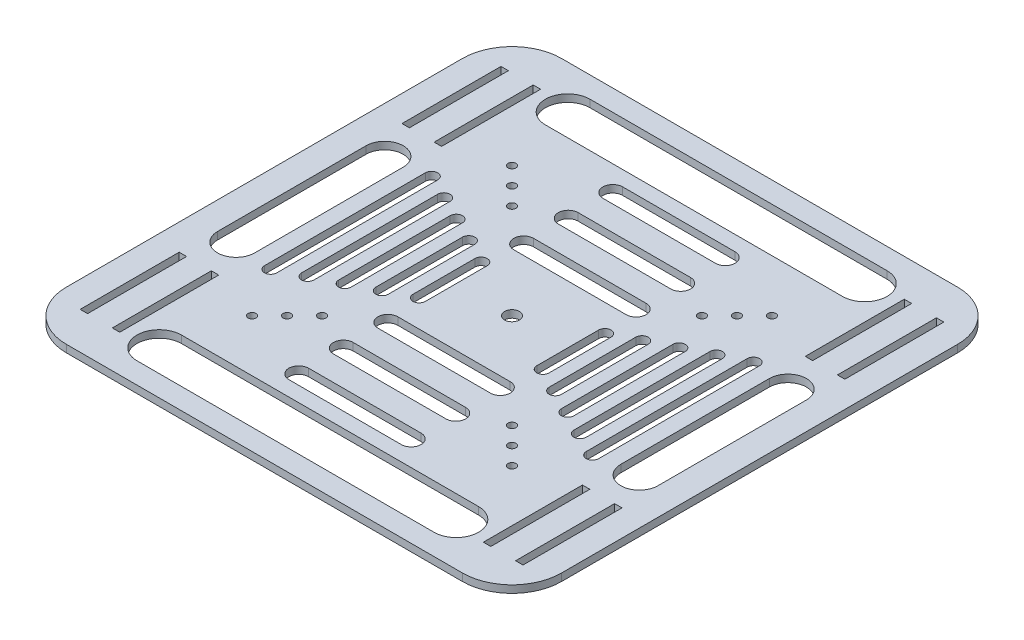
SolidWorks part; units mm, degrees
ref_plane "前视基准面" through (0, 0, 0) normal (0, 0, 1) x (1, 0, 0)
ref_plane "上视基准面" through (0, 0, 0) normal (0, 1, 0) x (1, 0, 0)
ref_plane "右视基准面" through (0, 0, 0) normal (1, 0, 0) x (0, 0, -1)
sketch "草图2" plane through (0, 0, 0) normal (0, 1, 0) x (1, 0, 0)
  line L0 (100, 100) -> (100, -100)
  line L1 (100, 100) -> (-100, 100)
  line L2 (100, -100) -> (-100, -100)
  line L3 (-100, 100) -> (-100, -100)
  line L4 (100, 100) -> (-100, -100) construction
  line L5 (100, -100) -> (-100, 100) construction
  line L6 (0, 65) -> (0, -65) construction
  line L7 (-68.9429, -68.9429) -> (68.9429, 68.9429) construction
  line L8 (-68.9429, 68.9429) -> (68.9429, -68.9429) construction
  line L9 (68.9429, 68.9429) -> (68.9429, -68.9429)
  line L10 (-68.9429, -68.9429) -> (-68.9429, 68.9429)
  line L11 (68.9429, 68.9429) -> (-68.9429, 68.9429)
  line L12 (-68.9429, -68.9429) -> (68.9429, -68.9429)
  line L13 (68.9429, 0) -> (81.4429, 0)
  line L14 (81.4429, 10) -> (81.4429, -10) construction
  line L15 (81.4429, 0) -> (76.4429, 0) construction
  line L16 (86.4429, -10) -> (89.4429, -10) construction
  line L17 (76.4429, 10) -> (73.4429, 10) construction
  line L18 (76.4429, 10) -> (76.4429, -10) construction
  line L19 (76.4429, -10) -> (73.4429, -10) construction
  line L20 (73.4429, 10) -> (73.4429, -10) construction
  line L21 (89.4429, 10) -> (89.4429, -10) construction
  line L22 (86.4429, 10) -> (86.4429, -10) construction
  line L23 (86.4429, 10) -> (89.4429, 10) construction
  line L24 (0, -65) -> (0, -100)
  line L25 (-60, -82.5) -> (60, -82.5) construction
  line L34 (-60, 82.5) -> (60, 82.5) construction
  line L35 (-81.4429, -10) -> (-81.4429, 10) construction
  line L36 (-81.4429, 0) -> (-76.4429, 0) construction
  line L37 (-86.4429, 10) -> (-89.4429, 10) construction
  line L38 (-76.4429, -10) -> (-73.4429, -10) construction
  line L39 (-76.4429, -10) -> (-76.4429, 10) construction
  line L40 (-76.4429, 10) -> (-73.4429, 10) construction
  line L41 (-73.4429, -10) -> (-73.4429, 10) construction
  line L42 (-89.4429, -10) -> (-89.4429, 10) construction
  line L43 (-86.4429, -10) -> (-86.4429, 10) construction
  line L44 (-86.4429, -10) -> (-89.4429, -10) construction
  line L45 (-60, 73.5) -> (60, 73.5)
  line L46 (-60, -73.5) -> (60, -73.5)
  line L47 (-60, -91.5) -> (60, -91.5)
  line L57 (0, 65) -> (73.4429, 65) construction
  line L58 (73.4429, 85) -> (73.4429, 45)
  line L59 (73.4429, 85) -> (76.4429, 85)
  line L60 (76.4429, 85) -> (76.4429, 45)
  line L61 (76.4429, 45) -> (73.4429, 45)
  line L62 (86.4429, 45) -> (89.4429, 45)
  line L63 (86.4429, 85) -> (86.4429, 45)
  line L64 (89.4429, 85) -> (86.4429, 85)
  line L65 (89.4429, 85) -> (89.4429, 45)
  line L66 (73.4429, -85) -> (73.4429, -45)
  line L67 (89.4429, -85) -> (89.4429, -45)
  line L68 (89.4429, -85) -> (86.4429, -85)
  line L69 (86.4429, -85) -> (86.4429, -45)
  line L70 (86.4429, -45) -> (89.4429, -45)
  line L71 (76.4429, -45) -> (73.4429, -45)
  line L72 (76.4429, -85) -> (76.4429, -45)
  line L73 (73.4429, -85) -> (76.4429, -85)
  line L74 (-73.4429, -85) -> (-76.4429, -85)
  line L75 (-76.4429, -85) -> (-76.4429, -45)
  line L76 (-76.4429, -45) -> (-73.4429, -45)
  line L77 (-86.4429, -45) -> (-89.4429, -45)
  line L78 (-86.4429, -85) -> (-86.4429, -45)
  line L79 (-89.4429, -85) -> (-86.4429, -85)
  line L80 (-89.4429, -85) -> (-89.4429, -45)
  line L81 (-73.4429, -85) -> (-73.4429, -45)
  line L82 (-89.4429, 85) -> (-89.4429, 45)
  line L83 (-89.4429, 85) -> (-86.4429, 85)
  line L84 (-86.4429, 85) -> (-86.4429, 45)
  line L85 (-86.4429, 45) -> (-89.4429, 45)
  line L86 (-76.4429, 45) -> (-73.4429, 45)
  line L87 (-76.4429, 85) -> (-76.4429, 45)
  line L88 (-73.4429, 85) -> (-76.4429, 85)
  line L89 (-73.4429, 85) -> (-73.4429, 45)
  line L90 (22.7145, 27.4289) -> (-22.7145, 27.4289) construction
  line L91 (22.7145, 23.4289) -> (-22.7145, 23.4289)
  line L96 (-45.4289, 45.4289) -> (0, 45.4289)
  line L99 (22.7145, 31.4289) -> (-22.7145, 31.4289)
  line L102 (22.7145, 63.4289) -> (-22.7145, 63.4289) construction
  line L108 (0, 0) -> (-52.5, 0)
  line L111 (-10, 86.4429) -> (10, 86.4429) [skipped]
  line L112 (-10, 81.4429) -> (10, 81.4429) [skipped]
  line L113 (0, 81.4429) -> (0, 76.4429) [skipped]
  line L114 (10, 86.4429) -> (10, 89.4429) [skipped]
  line L115 (-10, 76.4429) -> (-10, 73.4429) [skipped]
  line L116 (-10, 76.4429) -> (10, 76.4429) [skipped]
  line L117 (10, 76.4429) -> (10, 73.4429) [skipped]
  line L118 (-10, 73.4429) -> (10, 73.4429) [skipped]
  line L119 (-10, 89.4429) -> (10, 89.4429) [skipped]
  line L120 (-10, 86.4429) -> (-10, 89.4429) [skipped]
  line L121 (0, 68.9429) -> (0, 81.4429) construction
  line L122 (10, -81.4429) -> (-10, -81.4429) [skipped]
  line L123 (0, -81.4429) -> (0, -76.4429) [skipped]
  line L124 (-10, -86.4429) -> (-10, -89.4429) [skipped]
  line L125 (10, -76.4429) -> (-10, -76.4429) [skipped]
  line L126 (10, -89.4429) -> (-10, -89.4429) [skipped]
  line L127 (10, -86.4429) -> (-10, -86.4429) [skipped]
  line L128 (10, -86.4429) -> (10, -89.4429) [skipped]
  line L129 (10, -76.4429) -> (10, -73.4429) [skipped]
  line L130 (-10, -76.4429) -> (-10, -73.4429) [skipped]
  line L131 (10, -73.4429) -> (-10, -73.4429) [skipped]
  line L132 (0, -68.9429) -> (0, -81.4429) construction
  line L135 (22.7145, 45.4289) -> (-22.7145, 45.4289) construction
  line L136 (22.7145, 41.4289) -> (-22.7145, 41.4289)
  line L137 (-52.5, 0) -> (-52.5, 52.5)
  line L138 (22.7145, 49.4289) -> (-22.7145, 49.4289)
  line L139 (22.7145, 59.4289) -> (-22.7145, 59.4289)
  line L144 (22.7145, 67.4289) -> (-22.7145, 67.4289)
  line L147 (22.7145, -27.4289) -> (-22.7145, -27.4289) construction
  line L150 (22.7145, -23.4289) -> (-22.7145, -23.4289)
  line L153 (22.7145, -31.4289) -> (-22.7145, -31.4289)
  line L156 (22.7145, -45.4289) -> (-22.7145, -45.4289) construction
  line L159 (22.7145, -41.4289) -> (-22.7145, -41.4289)
  line L162 (22.7145, -49.4289) -> (-22.7145, -49.4289)
  line L165 (22.7145, -63.4289) -> (-22.7145, -63.4289) construction
  line L168 (22.7145, -59.4289) -> (-22.7145, -59.4289)
  line L169 (22.7145, -67.4289) -> (-22.7145, -67.4289)
  line L170 (0, 0) -> (25, 0)
  line L171 (25, 0) -> (25, 25)
  line L172 (25, 0) -> (35, 0)
  line L177 (35, 0) -> (45, 0)
  line L180 (45, 0) -> (55, 0)
  line L183 (55, 0) -> (65, 0)
  line L184 (65, 0) -> (65, 65)
  line L185 (55, 0) -> (55, 55)
  line L186 (45, 0) -> (45, 45)
  line L187 (35, 0) -> (35, 35)
  line L188 (25, -12.5) -> (25, 12.5) construction
  line L189 (22.5, -12.5) -> (22.5, 12.5)
  line L190 (27.5, -12.5) -> (27.5, 12.5)
  line L191 (35, -17.5) -> (35, 17.5) construction
  line L192 (32.5, -17.5) -> (32.5, 17.5)
  line L193 (37.5, -17.5) -> (37.5, 17.5)
  line L194 (45, -22.5) -> (45, 22.5) construction
  line L195 (42.5, -22.5) -> (42.5, 22.5)
  line L196 (47.5, -22.5) -> (47.5, 22.5)
  line L197 (55, -27.5) -> (55, 27.5) construction
  line L198 (52.5, -27.5) -> (52.5, 27.5)
  line L199 (57.5, -27.5) -> (57.5, 27.5)
  line L200 (65, -32.5) -> (65, 32.5) construction
  line L201 (62.5, -32.5) -> (62.5, 32.5)
  line L202 (67.5, -32.5) -> (67.5, 32.5)
  line L203 (-25, -12.5) -> (-25, 12.5) construction
  line L204 (-22.5, -12.5) -> (-22.5, 12.5)
  line L205 (-27.5, -12.5) -> (-27.5, 12.5)
  line L206 (-35, -17.5) -> (-35, 17.5) construction
  line L207 (-32.5, -17.5) -> (-32.5, 17.5)
  line L208 (-37.5, -17.5) -> (-37.5, 17.5)
  line L209 (-45, -22.5) -> (-45, 22.5) construction
  line L210 (-42.5, -22.5) -> (-42.5, 22.5)
  line L211 (-47.5, -22.5) -> (-47.5, 22.5)
  line L212 (-55, -27.5) -> (-55, 27.5) construction
  line L213 (-52.5, -27.5) -> (-52.5, 27.5)
  line L214 (-57.5, -27.5) -> (-57.5, 27.5)
  line L215 (-65, -32.5) -> (-65, 32.5) construction
  line L216 (-62.5, -32.5) -> (-62.5, 32.5)
  line L217 (-67.5, -32.5) -> (-67.5, 32.5)
  line L218 (-68.9429, 0) -> (-81.4429, 0) construction
  line L219 (-60, 91.5) -> (60, 91.5)
  line L220 (81.4429, 30) -> (81.4429, -30) construction
  line L221 (-81.4429, 30) -> (-81.4429, -30) construction
  line L222 (88.9429, 30) -> (88.9429, -30)
  line L223 (73.9429, 30) -> (73.9429, -30)
  line L224 (-88.9429, 30) -> (-88.9429, -30)
  line L225 (-73.9429, 30) -> (-73.9429, -30)
  arc A14 (-60, -73.5) -> (-60, -91.5) centre (-60, -82.5) ccw
  arc A15 (60, -91.5) -> (60, -73.5) centre (60, -82.5) ccw
  circle A18 centre (-52.5, 52.5) radius 1.6
  circle A19 centre (-45.4289, 45.4289) radius 1.6
  circle A20 centre (-38.3579, 38.3579) radius 1.6
  circle A21 centre (52.5, 52.5) radius 1.6
  circle A22 centre (45.4289, 45.4289) radius 1.6
  circle A23 centre (38.3579, 38.3579) radius 1.6
  circle A24 centre (52.5, -52.5) radius 1.6
  circle A25 centre (45.4289, -45.4289) radius 1.6
  circle A26 centre (38.3579, -38.3579) radius 1.6
  circle A27 centre (-52.5, -52.5) radius 1.6
  circle A28 centre (-45.4289, -45.4289) radius 1.6
  circle A29 centre (-38.3579, -38.3579) radius 1.6
  arc A32 (22.7145, 41.4289) -> (22.7145, 49.4289) centre (22.7145, 45.4289) ccw
  arc A33 (-22.7145, 49.4289) -> (-22.7145, 41.4289) centre (-22.7145, 45.4289) ccw
  circle A54 centre (0, 0) radius 12.5 construction
  arc A55 (22.7145, 23.4289) -> (22.7145, 31.4289) centre (22.7145, 27.4289) ccw
  arc A56 (-22.7145, 31.4289) -> (-22.7145, 23.4289) centre (-22.7145, 27.4289) ccw
  arc A57 (22.7145, 59.4289) -> (22.7145, 67.4289) centre (22.7145, 63.4289) ccw
  arc A58 (-22.7145, 67.4289) -> (-22.7145, 59.4289) centre (-22.7145, 63.4289) ccw
  arc A59 (22.7145, -23.4289) -> (22.7145, -31.4289) centre (22.7145, -27.4289) cw
  arc A60 (-22.7145, -31.4289) -> (-22.7145, -23.4289) centre (-22.7145, -27.4289) cw
  arc A61 (22.7145, -41.4289) -> (22.7145, -49.4289) centre (22.7145, -45.4289) cw
  arc A62 (-22.7145, -49.4289) -> (-22.7145, -41.4289) centre (-22.7145, -45.4289) cw
  arc A63 (22.7145, -59.4289) -> (22.7145, -67.4289) centre (22.7145, -63.4289) cw
  arc A64 (-22.7145, -67.4289) -> (-22.7145, -59.4289) centre (-22.7145, -63.4289) cw
  arc A73 (22.5, -12.5) -> (27.5, -12.5) centre (25, -12.5) ccw
  arc A74 (27.5, 12.5) -> (22.5, 12.5) centre (25, 12.5) ccw
  arc A75 (32.5, -17.5) -> (37.5, -17.5) centre (35, -17.5) ccw
  arc A76 (37.5, 17.5) -> (32.5, 17.5) centre (35, 17.5) ccw
  arc A77 (42.5, -22.5) -> (47.5, -22.5) centre (45, -22.5) ccw
  arc A78 (47.5, 22.5) -> (42.5, 22.5) centre (45, 22.5) ccw
  arc A79 (52.5, -27.5) -> (57.5, -27.5) centre (55, -27.5) ccw
  arc A80 (57.5, 27.5) -> (52.5, 27.5) centre (55, 27.5) ccw
  arc A81 (62.5, -32.5) -> (67.5, -32.5) centre (65, -32.5) ccw
  arc A82 (67.5, 32.5) -> (62.5, 32.5) centre (65, 32.5) ccw
  arc A83 (-22.5, -12.5) -> (-27.5, -12.5) centre (-25, -12.5) cw
  arc A84 (-27.5, 12.5) -> (-22.5, 12.5) centre (-25, 12.5) cw
  arc A85 (-32.5, -17.5) -> (-37.5, -17.5) centre (-35, -17.5) cw
  arc A86 (-37.5, 17.5) -> (-32.5, 17.5) centre (-35, 17.5) cw
  arc A87 (-42.5, -22.5) -> (-47.5, -22.5) centre (-45, -22.5) cw
  arc A88 (-47.5, 22.5) -> (-42.5, 22.5) centre (-45, 22.5) cw
  arc A89 (-52.5, -27.5) -> (-57.5, -27.5) centre (-55, -27.5) cw
  arc A90 (-57.5, 27.5) -> (-52.5, 27.5) centre (-55, 27.5) cw
  arc A91 (-62.5, -32.5) -> (-67.5, -32.5) centre (-65, -32.5) cw
  arc A92 (-67.5, 32.5) -> (-62.5, 32.5) centre (-65, 32.5) cw
  arc A106 (-60, 73.5) -> (-60, 91.5) centre (-60, 82.5) cw
  arc A107 (60, 91.5) -> (60, 73.5) centre (60, 82.5) cw
  arc A108 (88.9429, 30) -> (73.9429, 30) centre (81.4429, 30) ccw
  arc A109 (73.9429, -30) -> (88.9429, -30) centre (81.4429, -30) ccw
  arc A110 (-88.9429, 30) -> (-73.9429, 30) centre (-81.4429, 30) cw
  arc A111 (-73.9429, -30) -> (-88.9429, -30) centre (-81.4429, -30) cw
  circle A112 centre (0, 0) radius 3
  point P1 (0, 0)
  point P4 (0, 0)
  point P7 (0, 0)
  point P15 (0, 0)
  point P20 (81.4429, 0)
  point P35 (0, -81.4429)
  point P38 (0, -82.5)
  point P43 (0, 82.5)
  point P51 (-81.4429, 0)
  point P62 (0, 81.4429)
  point P74 (0, 0)
  point P76 (73.4429, 65)
  point P82 (89.4429, 65)
  point P91 (89.4429, -65)
  point P100 (-89.4429, -65)
  point P109 (-89.4429, 65)
  point P110 (-73.4429, 65)
  point P115 (0, 27.4289)
  point P136 (0, 0)
  point P139 (0, 63.4289)
  point P145 (0, 45.4289)
  point P152 (0, -27.4289)
  point P159 (0, -45.4289)
  point P210 (0, -63.4289)
  point P227 (25, 0)
  point P233 (35, 0)
  point P241 (45, 0)
  point P247 (55, 0)
  point P254 (65, 0)
  point P261 (0, 0)
  point P263 (-25, 0)
  point P270 (-35, 0)
  point P277 (-45, 0)
  point P284 (-55, 0)
  point P291 (-65, 0)
  point P299 (81.4429, 0)
  point P304 (-81.4429, 0)
  dimension "D10" = 3.2
  dimension "D15" = 25
  dimension "D14" = 2
  dimension "D22" = 6
  dimension "D1" = 200
  dimension "D2" = 200
  dimension "D3" = 12.5
  dimension "D4" = 10
  dimension "D5" = 5
  dimension "D6" = 20
  dimension "D7" = 3
  dimension "D8" = 4
  dimension "D9" = 20
  dimension "D12" = 52.5
  dimension "D13" = 4
  dimension "D17" = 25
  dimension "D18" = 10
  dimension "D19" = 10
  dimension "D20" = 10
  dimension "D21" = 10
  dimension "D11" = 3
  dimension "D16" = 2
extrude "凸台-拉伸1" add sketch "草图2" along normal blind 3
fillet "圆角2" radius 20 4 edges at (-100, 1.5, -100) (100, 1.5, -100) (100, 1.5, 100) (-100, 1.5, 100)
